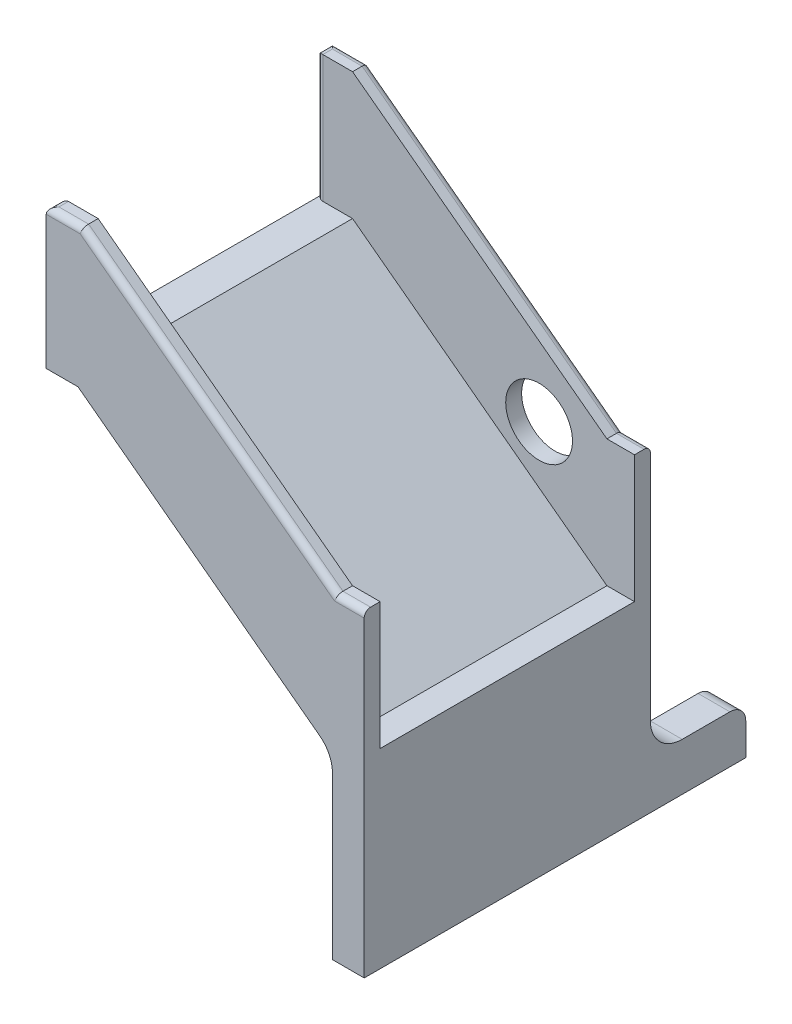
SolidWorks part; units mm, degrees
ref_plane "Front Plane" through (0, 0, 0) normal (0, 0, 1) x (1, 0, 0)
ref_plane "Top Plane" through (0, 0, 0) normal (0, 1, 0) x (1, 0, 0)
ref_plane "Right Plane" through (0, 0, 0) normal (1, 0, 0) x (0, 0, -1)
sketch "Sketch1" plane through (0, 0, 0) normal (0, 0, 1) x (1, 0, 0)
  line L0 (-38.322, 0) -> (41.678, 0) construction
  line L1 (41.678, 0) -> (-38.322, 60)
  line L2 (-38.322, 60) -> (-38.322, 0) construction
  line L3 (-38.322, 60) -> (-48.322, 60)
  line L4 (-48.322, 60) -> (-48.322, 64)
  line L5 (-48.322, 64) -> (-36.9887, 64)
  line L6 (-36.9887, 64) -> (43.0113, 4)
  line L7 (43.0113, 4) -> (51.678, 4)
  line L8 (51.678, 4) -> (51.678, 0)
  line L9 (51.678, 0) -> (41.678, 0)
  dimension "D1" = 80
  dimension "D2" = 60
  dimension "D3" = 4
  dimension "D4" = 4
  dimension "D5" = 4
  dimension "D6" = 10
  dimension "D7" = 10
extrude "Boss-Extrude1" add sketch "Sketch1" along normal mid plane 90
sketch "Sketch2" plane through (0, 0, 45) normal (0, 0, 1) x (1, 0, 0)
  line L0 (-48.322, 64) -> (-48.322, 104)
  line L1 (-48.322, 104) -> (-36.9887, 104)
  line L2 (-36.9887, 104) -> (43.0113, 44)
  line L3 (43.0113, 44) -> (51.678, 44)
  line L4 (51.678, 44) -> (51.678, 4)
  line L5 (51.678, 4) -> (43.0113, 4)
  line L6 (43.0113, 4) -> (-36.9887, 64)
  line L7 (-36.9887, 64) -> (-48.322, 64)
  dimension "D1" = 40
extrude "Boss-Extrude2" add sketch "Sketch2" against normal blind 5
mirror "Mirror1" about plane through (0, 0, 0) normal (0, 0, 1) of "Boss-Extrude2"
sketch "Sketch3" plane through (0, 0, -45) normal (0, 0, -1) x (-1, 0, 0)
  line L0 (-51.678, 0) -> (-51.678, 44) construction
  line L1 (-41.678, 0) -> (-51.678, 0) construction
  circle A0 centre (-21.678, 38) radius 10.5
  point P4 (0, 0)
  dimension "D1" = 21
  dimension "D2" = 30
  dimension "D3" = 38
extrude "Cut-Extrude1" cut sketch "Sketch3" against normal up to next
sketch "Sketch5" plane through (-48.322, 0, 0) normal (-1, 0, 0) x (0, 0, 1)
  line L0 (-10, 60) -> (10, 60)
  line L1 (45, 60) -> (-45, 60) construction
  line L2 (10, 60) -> (10, 30)
  line L3 (10, 30) -> (-10, 30)
  line L4 (-10, 30) -> (-10, 60)
  point P4 (0, 30)
  dimension "D1" = 20
  dimension "D2" = 30
  dimension "D3" = 0
extrude "Boss-Extrude3" add sketch "Sketch5" against normal blind 10
sketch "Sketch6" plane through (-48.322, 0, 0) normal (-1, 0, 0) x (0, 0, 1)
  line L0 (40, 64) -> (-40, 64) construction
  circle A0 centre (0, 44) radius 5.0873
  dimension "D1" = 20
extrude "Cut-Extrude2" cut sketch "Sketch6" against normal blind 10
sketch "Sketch8" plane through (0, 0, 45) normal (0, 0, 1) x (1, 0, 0)
  line L0 (41.678, 0) -> (51.678, 0)
  line L1 (51.678, 0) -> (51.678, -56)
  line L2 (41.678, 0) -> (41.678, -56)
  line L3 (41.678, -56) -> (51.678, -56)
  dimension "D1" = 56
extrude "Boss-Extrude4" add sketch "Sketch8" against normal blind 90
fillet "Fillet1" radius 10 2 edges at (-43.322, 60, 10) (-43.322, 60, -10)
fillet "Fillet2" radius 10 1 edges at (41.678, 0, 0)
fillet "Fillet3" radius 2 10 edges at (47.3446, 44, 45) (47.3446, 44, -45) (-42.6554, 104, -45) (3.0113, 74, -45) (3.0113, 74, 45) (-42.6554, 104, 45) (-48.322, 104, -42.5) (-48.322, 104, 42.5) (-48.322, 84, -40) (-48.322, 84, 40)
sketch "Sketch9" plane through (0, 0, -45) normal (0, 0, -1) x (-1, 0, 0)
  line L0 (-41.678, -5) -> (-41.678, -56) construction
  line L1 (-51.678, -56) -> (-41.678, -56)
  line L2 (-51.678, -56) -> (-51.678, -41)
  line L3 (-51.678, -41) -> (-41.678, -41)
  line L4 (-41.678, -56) -> (-41.678, -41)
  dimension "D1" = 15
extrude "Boss-Extrude5" add sketch "Sketch9" along normal blind 30
fillet "Fillet4" radius 10 1 edges at (46.678, -41, -45)
fillet "Fillet5" radius 5 1 edges at (46.678, -41, -75)
